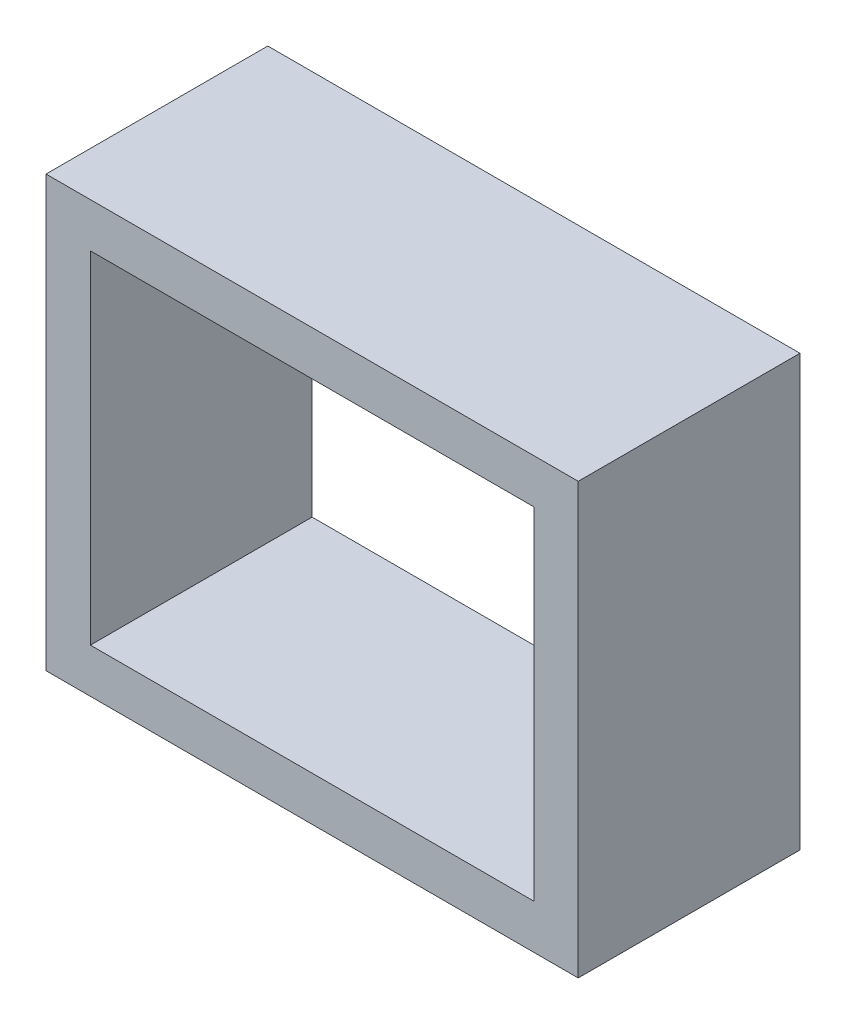
SolidWorks part; units mm, degrees
material "ABS"
ref_plane "Front Plane" through (0, 0, 0) normal (0, 0, 1) x (1, 0, 0)
ref_plane "Top Plane" through (0, 0, 0) normal (0, 1, 0) x (1, 0, 0)
ref_plane "Right Plane" through (0, 0, 0) normal (1, 0, 0) x (0, 0, -1)
sketch "Sketch1" plane through (0, 0, 0) normal (0, 0, 1) x (1, 0, 0)
  line L1 (-50, 36.6667) -> (50, 36.6667)
  line L2 (-50, 36.6667) -> (-50, -40.3333)
  line L3 (-50, -40.3333) -> (50, -40.3333)
  line L4 (50, 36.6667) -> (50, -40.3333)
  dimension "D1" = 100
  dimension "D2" = 77
extrude "Extrude-Thin1" add sketch "Sketch1" along normal blind 50 thin thin type one direction wall 10
sketch "Sketch2" plane through (0, 0, 50) normal (0, 0, 1) x (1, 0, 0)
  line L1 (-60, 46.6667) -> (60, 46.6667)
  line L2 (-60, 46.6667) -> (-60, -50.3333)
  line L3 (-60, -50.3333) -> (60, -50.3333)
  line L4 (60, 46.6667) -> (60, -50.3333)
